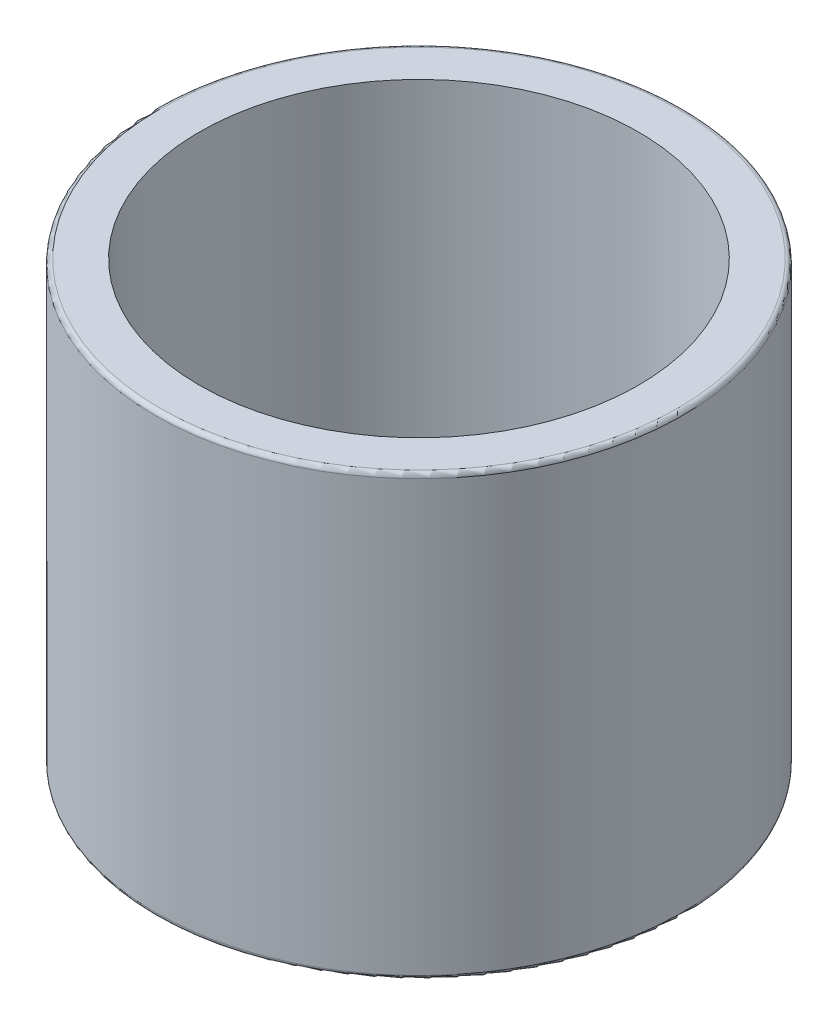
SolidWorks part; units mm, degrees
material "ABS"
ref_plane "Ebene vorne" through (0, 0, 0) normal (0, 0, 1) x (1, 0, 0)
ref_plane "Ebene oben" through (0, 0, 0) normal (0, 1, 0) x (1, 0, 0)
ref_plane "Ebene rechts" through (0, 0, 0) normal (1, 0, 0) x (0, 0, -1)
sketch "Skizze1" plane through (0, 0, 0) normal (0, 1, 0) x (1, 0, 0)
  circle A0 centre (0, 0) radius 5
  circle A1 centre (0, 0) radius 6
  dimension "D1" = 10
  dimension "D2" = 1
extrude "Aufsatz-Linear austragen1" add sketch "Skizze1" along normal mid plane 10
fillet "Verrundung1" radius 0.1 2 edges at (0, -5, 6) (0, 5, 6)
